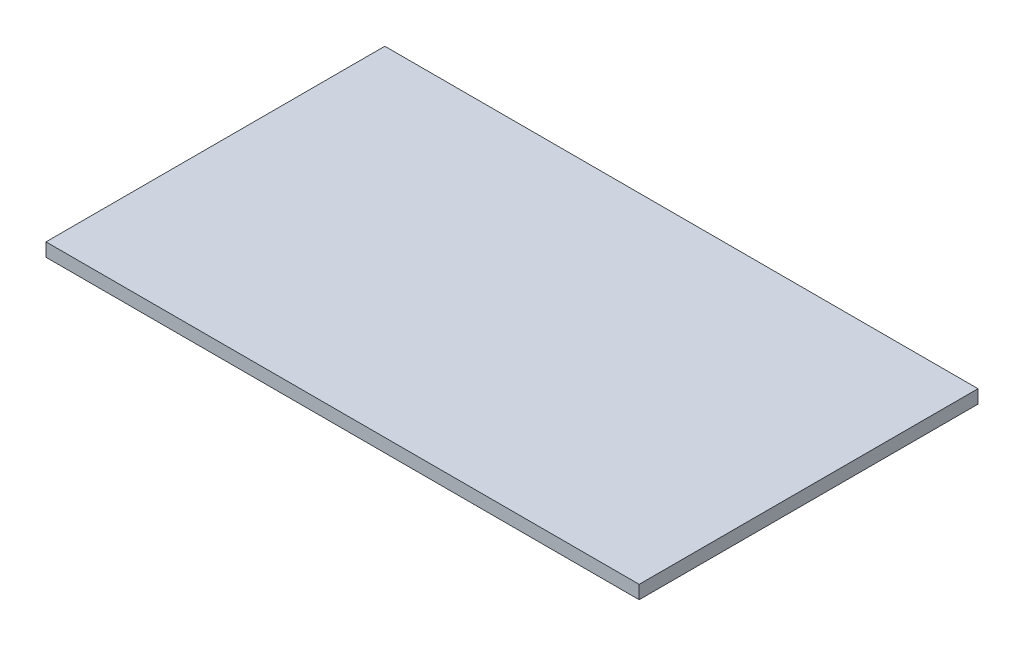
SolidWorks part; units mm, degrees
ref_plane "Front Plane" through (0, 0, 0) normal (0, 0, 1) x (1, 0, 0)
ref_plane "Top Plane" through (0, 0, 0) normal (0, 1, 0) x (1, 0, 0)
ref_plane "Right Plane" through (0, 0, 0) normal (1, 0, 0) x (0, 0, -1)
sketch "Sketch1" plane through (0, 0, 0) normal (0, 1, 0) x (1, 0, 0)
  line L1 (-214.3598, 36.9171) -> (154.7657, 36.9171)
  line L2 (-214.3598, 36.9171) -> (-214.3598, -173.9283)
  line L3 (-214.3598, -173.9283) -> (154.7657, -173.9283)
  line L4 (154.7657, 36.9171) -> (154.7657, -173.9283)
  dimension "D1" = 369.1255
  dimension "D2" = 210.8454
extrude "Boss-Extrude1" add sketch "Sketch1" along normal blind 8.3312
equation "\"D2@Sketch1\"=\"Base Width@Assembled Container.Assembly\""
equation "\"D1@Sketch1\"=\"Base Length@Assembled Container.Assembly\""
equation "\"D1@Boss-Extrude1\"=\"Acrylic Thickness@Assembled Container.Assembly\""
